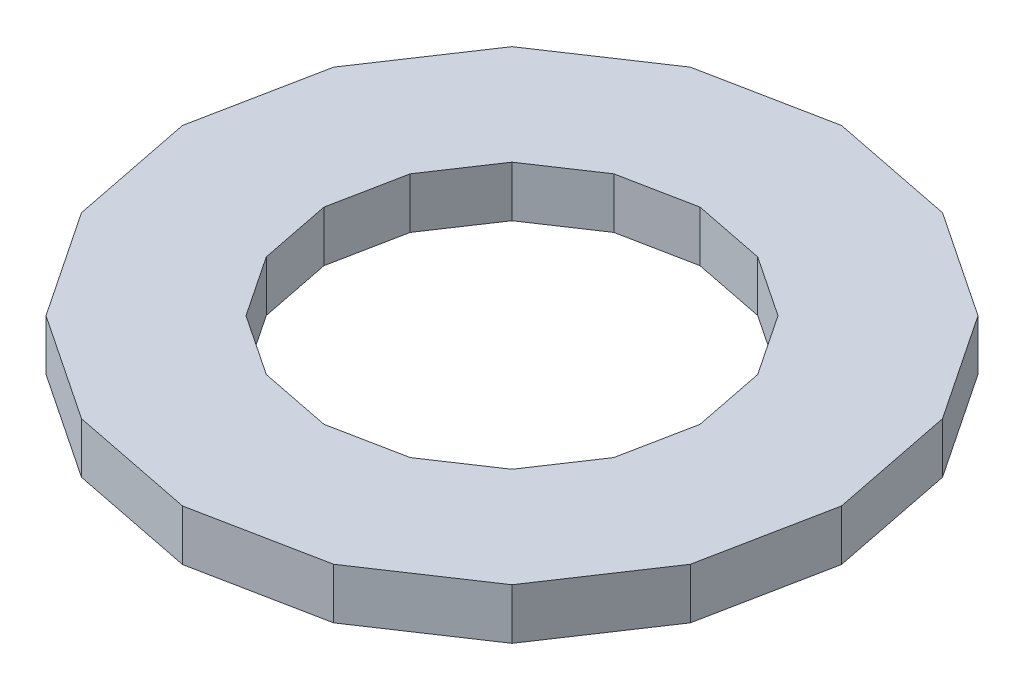
SolidWorks part; units mm, degrees
ref_plane "Front Plane" through (0, 0, 0) normal (0, 0, 1) x (1, 0, 0)
ref_plane "Top Plane" through (0, 0, 0) normal (0, 1, 0) x (1, 0, 0)
ref_plane "Right Plane" through (0, 0, 0) normal (1, 0, 0) x (0, 0, -1)
sketch "Sketch1" plane through (0, 0, 0) normal (0, 1, 0) x (1, 0, 0)
  line L1 (70.5962, 0) -> (65.2224, 27.016)
  line L2 (65.2224, 27.016) -> (49.919, 49.919)
  line L3 (49.919, 49.919) -> (27.016, 65.2224)
  line L4 (27.016, 65.2224) -> (0, 70.5962)
  line L5 (0, 70.5962) -> (-27.016, 65.2224)
  line L6 (-27.016, 65.2224) -> (-49.919, 49.919)
  line L7 (-49.919, 49.919) -> (-65.2224, 27.016)
  line L8 (-65.2224, 27.016) -> (-70.5962, 0)
  line L9 (-70.5962, 0) -> (-65.2224, -27.016)
  line L10 (-65.2224, -27.016) -> (-49.919, -49.919)
  line L11 (-49.919, -49.919) -> (-27.016, -65.2224)
  line L12 (-27.016, -65.2224) -> (0, -70.5962)
  line L13 (0, -70.5962) -> (27.016, -65.2224)
  line L14 (27.016, -65.2224) -> (49.919, -49.919)
  line L15 (49.919, -49.919) -> (65.2224, -27.016)
  line L16 (65.2224, -27.016) -> (70.5962, 0)
  line L17 (123.6863, 0) -> (114.2712, 47.3327)
  line L18 (114.2712, 47.3327) -> (87.4594, 87.4594)
  line L19 (87.4594, 87.4594) -> (47.3327, 114.2712)
  line L20 (47.3327, 114.2712) -> (0, 123.6863)
  line L21 (0, 123.6863) -> (-47.3327, 114.2712)
  line L22 (-47.3327, 114.2712) -> (-87.4594, 87.4594)
  line L23 (-87.4594, 87.4594) -> (-114.2712, 47.3327)
  line L24 (-114.2712, 47.3327) -> (-123.6863, 0)
  line L25 (-123.6863, 0) -> (-114.2712, -47.3327)
  line L26 (-114.2712, -47.3327) -> (-87.4594, -87.4594)
  line L27 (-87.4594, -87.4594) -> (-47.3327, -114.2712)
  line L28 (-47.3327, -114.2712) -> (0, -123.6863)
  line L29 (0, -123.6863) -> (47.3327, -114.2712)
  line L30 (47.3327, -114.2712) -> (87.4594, -87.4594)
  line L31 (87.4594, -87.4594) -> (114.2712, -47.3327)
  line L32 (114.2712, -47.3327) -> (123.6863, 0)
  circle A1 centre (0, 0) radius 69.2397 construction
  circle A2 centre (0, 0) radius 121.3097 construction
  dimension "D1" = 52.07
  dimension "D2" = 48.26
extrude "Boss-Extrude1" add sketch "Sketch1" along normal blind 19.05
